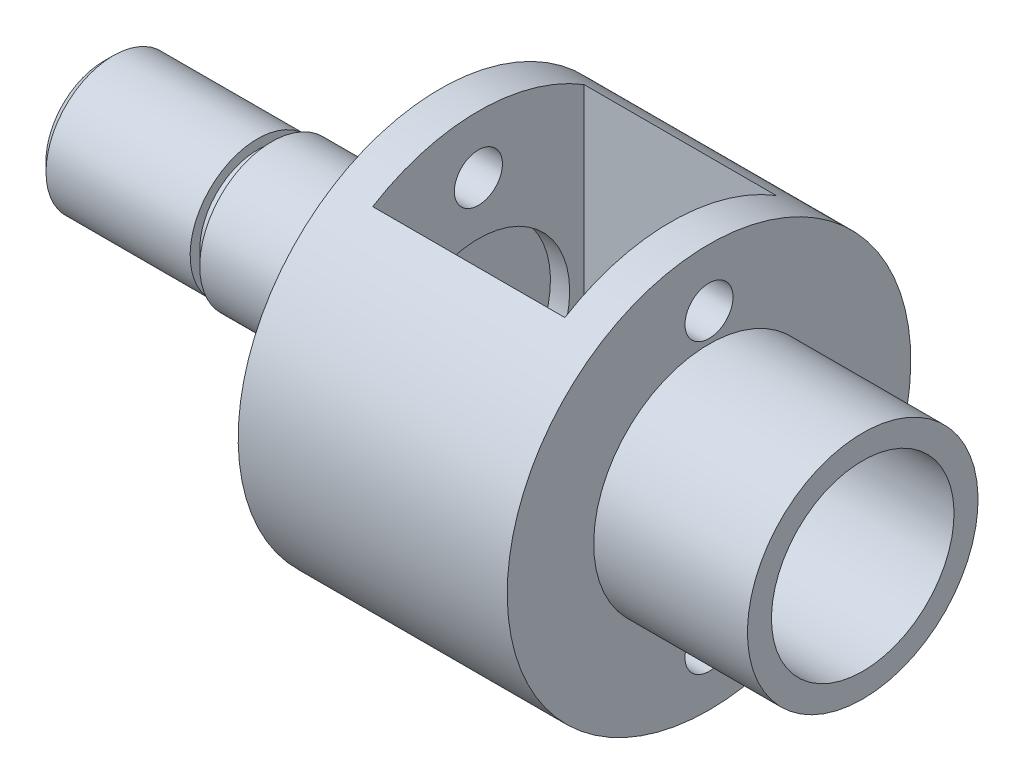
SolidWorks part; units mm, degrees
ref_plane "Plan de face" through (0, 0, 0) normal (0, 0, 1) x (1, 0, 0)
ref_plane "Plan de dessus" through (0, 0, 0) normal (0, 1, 0) x (1, 0, 0)
ref_plane "Plan de droite" through (0, 0, 0) normal (1, 0, 0) x (0, 0, -1)
sketch "Sketch2" plane through (0, 0, 0) normal (0, 0, 1) x (1, 0, 0)
  line L0 (0, 0) -> (0, 4.75) construction
  line L1 (0, 4.75) -> (0, 6)
  line L2 (0, 6) -> (-8, 6)
  line L3 (-8, 6) -> (-8, 10.5)
  line L4 (-8, 10.5) -> (-22, 10.5)
  line L5 (-22, 10.5) -> (-22, 6)
  line L6 (-22, 6) -> (-24.5, 6)
  line L7 (-24.5, 6) -> (-24.5, 3.75)
  line L8 (-24.5, 3.75) -> (-30.75, 3.75)
  line L9 (-30.75, 3.75) -> (-30.75, 3)
  line L10 (-30.75, 3) -> (-31.5, 3)
  line L11 (-31.5, 3) -> (-31.5, 3.5)
  line L12 (-31.5, 3.5) -> (-39.5, 3.5)
  line L13 (-39.5, 3.5) -> (-39.5, 0)
  line L14 (-21, 0) -> (-39.5, 0)
  line L15 (0, 4.75) -> (-21, 4.75)
  line L16 (-21, 4.75) -> (-21, 0)
  line L17 (-21, 0) -> (0, 0) construction
  point P15 (-39.5, 3.5)
  point P19 (0, 0)
  point P20 (-39.5, 3.5)
  point P21 (-39.4826, 3.5)
  point P22 (0, 0)
  dimension "D1" = 4.75
  dimension "D2" = 1.25
  dimension "D3" = 8
  dimension "D4" = 4.5
  dimension "D5" = 14
  dimension "D6" = 4.5
  dimension "D7" = 2.5
  dimension "D8" = 2.25
  dimension "D9" = 6.25
  dimension "D10" = 0.75
  dimension "D11" = 0.75
  dimension "D12" = 0.5
  dimension "D13" = 8
  dimension "D14" = 3.5
  dimension "D15" = 39.5
  dimension "D16" = 21
revolve "Revolve1" add sketch "Sketch2" angle 360 about L17
cosmetic thread "Cosmetic Thread2" parameters "D2"=6
sketch "Sketch6" plane through (-8, 0, 0) normal (1, 0, 0) x (0, 0, -1)
  line L0 (0, 0) -> (0, 7.5) construction
  line L2 (0, 0) -> (0, -7.5) construction
  point P0 (0, 7.5)
  point P20 (0, -7.5)
  point P26 (0, -7.5)
  dimension "D1" = 7.5
  dimension "D3" = 7.5
hole_wizard "Ø2.5 (2.5) Diameter Hole1" positions "Sketch6" profile "Sketch5" hole size "Ø2.5" standard "ANSI Metric" end condition up to next
sketch "Sketch5" plane through (-8, 7.5, 0) normal (0, 1, 0) x (0, 0, -1)
  line L0 (0, 0) -> (0, 14)
  line L1 (0, 14) -> (1.25, 14)
  line L2 (1.25, 14) -> (1.25, 0)
  line L5 (1.25, 0) -> (0, 0)
  line L11 (0, -6.35) -> (0, 107.95) construction
  dimension "Thru Hole Dia." = 2.5
  dimension "Thru Hole Depth" = 14
sketch "Sketch3" plane through (0, 0, 0) normal (0, 1, 0) x (1, 0, 0)
  line L0 (0, 0) -> (-10, 0) construction
  line L1 (0, -4.75) -> (0, 4.75) construction
  line L2 (-10, 0) -> (-20, 0) construction
  line L3 (-20, 5.5) -> (-20, -5.5)
  line L5 (-20, 5.5) -> (-10, 5.5)
  line L7 (-20, -5.5) -> (-10, -5.5)
  line L8 (-10, 5.5) -> (-10, -5.5)
  dimension "D1" = 10
  dimension "D2" = 10
  dimension "D4" = 11
extrude "Cut-Extrude1" cut sketch "Sketch3" against normal up to next and the other way up to next
chamfer "Chamfer1" distance 0.5 angle 45 1 edges at (-39.5, -3.5, 0)
